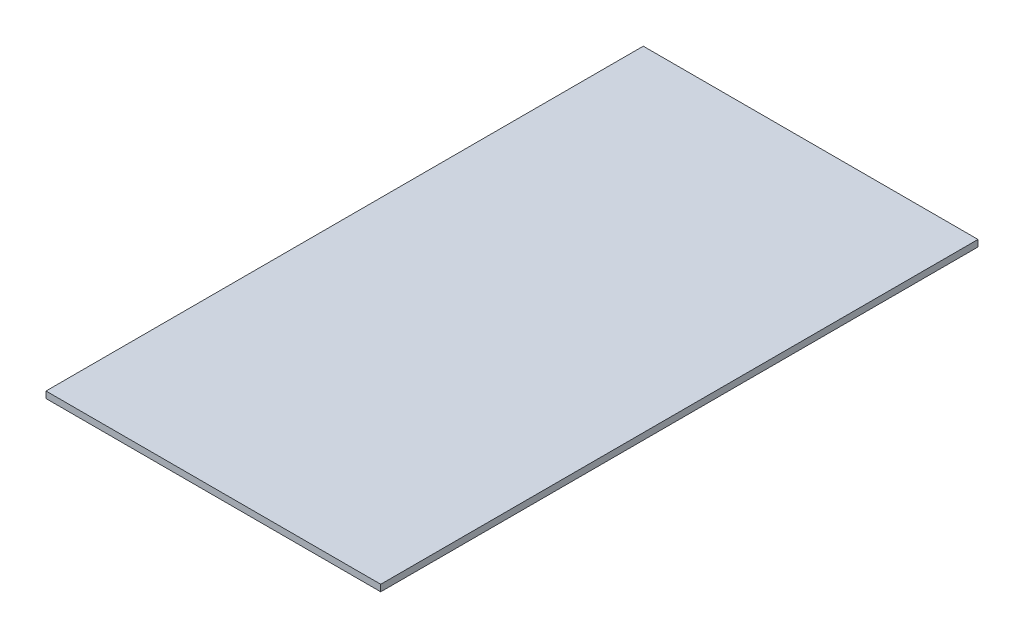
SolidWorks part; units mm, degrees
ref_plane "Front Plane" through (0, 0, 0) normal (0, 0, 1) x (1, 0, 0)
ref_plane "Top Plane" through (0, 0, 0) normal (0, 1, 0) x (1, 0, 0)
ref_plane "Right Plane" through (0, 0, 0) normal (1, 0, 0) x (0, 0, -1)
sketch "Sketch1" plane through (0, 0, 0) normal (0, 1, 0) x (1, 0, 0)
  line L20 (271.294, -171.6993) -> (271.294, 283.3007)
  line L21 (16.294, -171.6993) -> (271.294, -171.6993)
  line L22 (16.294, 283.3007) -> (16.294, -171.6993)
  line L23 (271.294, 283.3007) -> (16.294, 283.3007)
  line L24 (271.294, -171.6993) -> (271.294, 283.3007)
  line L25 (16.294, -171.6993) -> (271.294, -171.6993)
  line L26 (16.294, 283.3007) -> (16.294, -171.6993)
  line L27 (271.294, 283.3007) -> (16.294, 283.3007)
  dimension "D1" = 2.5
extrude "Boss-Extrude1" add sketch "Sketch1" against normal blind 5 from surface
